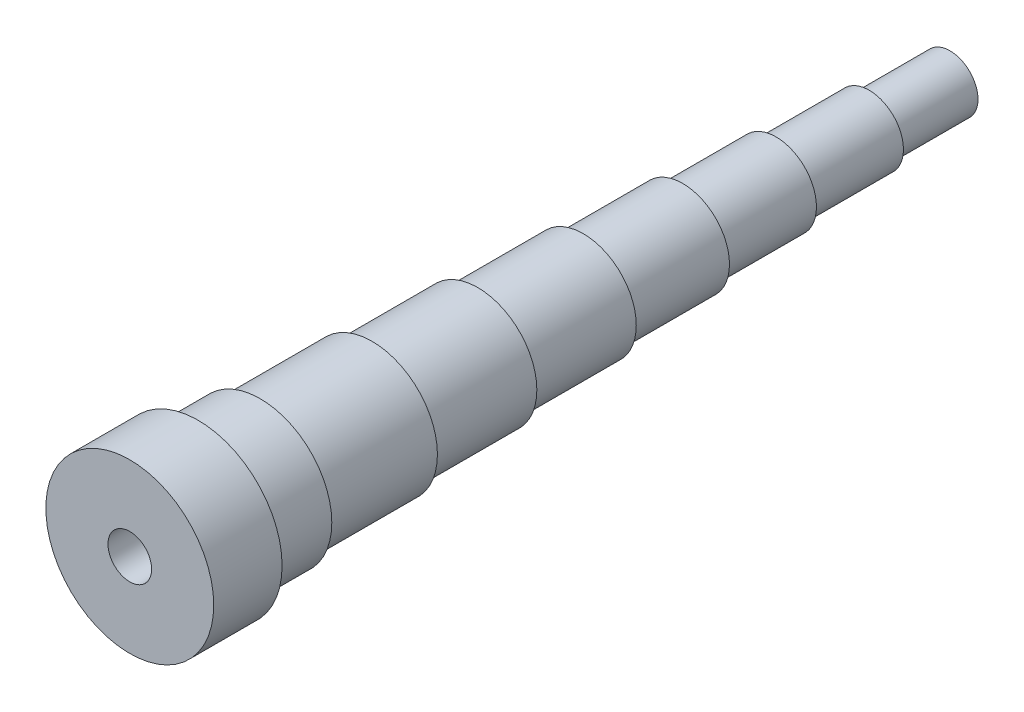
SolidWorks part; units mm, degrees
ref_plane "Front Plane" through (0, 0, 0) normal (0, 0, 1) x (1, 0, 0)
ref_plane "Top Plane" through (0, 0, 0) normal (0, 1, 0) x (1, 0, 0)
ref_plane "Right Plane" through (0, 0, 0) normal (1, 0, 0) x (0, 0, -1)
sketch "Sketch1" plane through (0, 0, 0) normal (1, 0, 0) x (0, 0, -1)
  line L0 (-19.9049, 0) -> (31.5847, 0) construction
  line L1 (-264.0381, 12.7) -> (213.4006, 12.7)
  line L2 (213.4006, 12.7) -> (213.4006, 16.317)
  line L3 (213.4006, 16.317) -> (166.3802, 16.317)
  line L4 (166.3802, 16.317) -> (166.3802, 19.9339)
  line L5 (166.3802, 19.9339) -> (112.1258, 19.9339)
  line L6 (112.1258, 19.9339) -> (112.1258, 23.5509)
  line L7 (112.1258, 23.5509) -> (57.8714, 23.5509)
  line L8 (57.8714, 23.5509) -> (57.8714, 27.1678)
  line L9 (57.8714, 27.1678) -> (0, 27.1678)
  line L10 (0, 27.1678) -> (0, 30.7848)
  line L11 (0, 30.7848) -> (-61.4883, 30.7848)
  line L12 (-61.4883, 30.7848) -> (-61.4883, 34.4018)
  line L13 (-61.4883, 34.4018) -> (-122.9766, 34.4018)
  line L14 (-122.9766, 34.4018) -> (-122.9766, 38.0187)
  line L15 (-122.9766, 38.0187) -> (-188.0819, 38.0187)
  line L16 (-264.0381, 38.0187) -> (-264.0381, 12.7)
  line L17 (-188.0819, 38.0187) -> (-188.0819, 41.6357)
  line L18 (-188.0819, 41.6357) -> (-224.2515, 41.6357)
  line L19 (-224.2515, 41.6357) -> (-224.2515, 48.8696)
  line L20 (-264.0381, 38.0187) -> (-264.0381, 48.8696)
  line L21 (-264.0381, 48.8696) -> (-224.2515, 48.8696)
  dimension "D1" = 12.7
  dimension "D2" = 477.4387
  dimension "D3" = 3.617
  dimension "D4" = 3.617
  dimension "D5" = 3.617
  dimension "D6" = 3.617
  dimension "D7" = 3.617
  dimension "D8" = 3.617
  dimension "D9" = 3.617
  dimension "D10" = 430.4182
  dimension "D11" = 376.1638
  dimension "D12" = 321.9094
  dimension "D13" = 264.0381
  dimension "D14" = 202.5498
  dimension "D15" = 3.617
  dimension "D16" = 7.2339
  dimension "D17" = 141.0614
  dimension "D18" = 75.9562
  dimension "D19" = 39.7866
revolve "Revolve1" add sketch "Sketch1" angle 360 about L0
